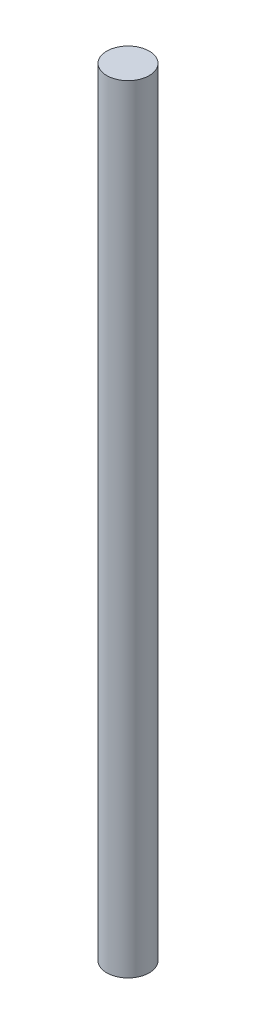
SolidWorks part; units mm, degrees
material "AISI 316 Stainless Steel Sheet (SS)"
ref_plane "Front Plane" through (0, 0, 0) normal (0, 0, 1) x (1, 0, 0)
ref_plane "Top Plane" through (0, 0, 0) normal (0, 1, 0) x (1, 0, 0)
ref_plane "Right Plane" through (0, 0, 0) normal (1, 0, 0) x (0, 0, -1)
sketch "Sketch1" plane through (0, 0, 0) normal (0, 1, 0) x (1, 0, 0)
  circle A0 centre (0, 0) radius 2.0828
  dimension "D1" = 4.1656
extrude "Boss-Extrude1" add sketch "Sketch1" along normal blind 76.2
cosmetic thread "Cosmetic Thread1"
